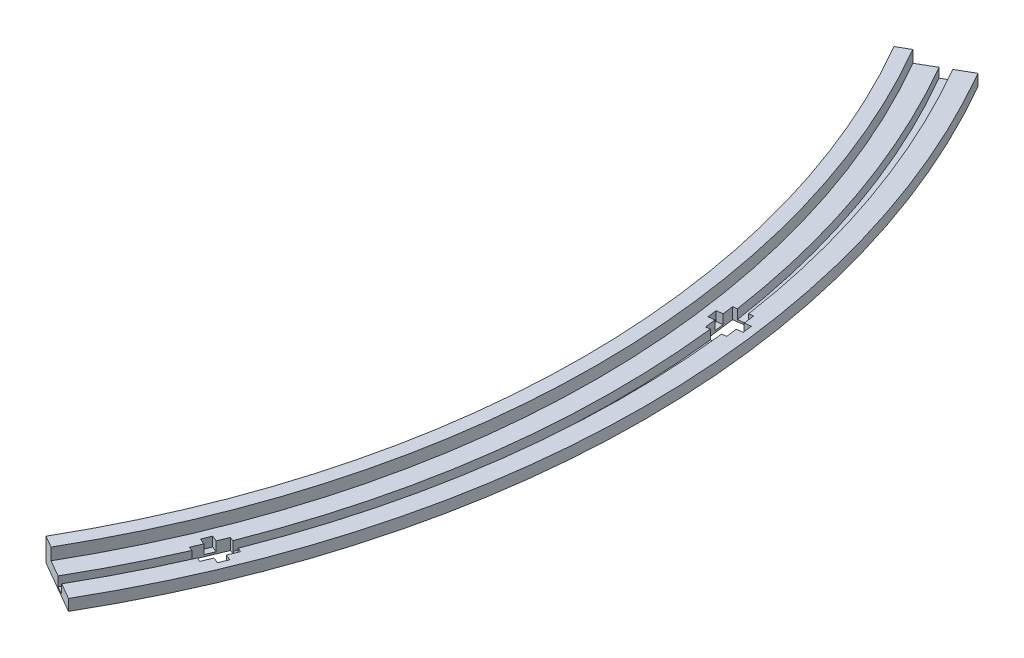
SolidWorks part; units mm, degrees
ref_plane "Ebene vorne" through (0, 0, 0) normal (0, 0, 1) x (1, 0, 0)
ref_plane "Ebene oben" through (0, 0, 0) normal (0, 1, 0) x (1, 0, 0)
ref_plane "Ebene rechts" through (0, 0, 0) normal (1, 0, 0) x (0, 0, -1)
sketch "Skizze1" plane through (0, 0, 0) normal (0, 1, 0) x (1, 0, 0)
  line L0 (0, 0) -> (290, 0) construction
  line L1 (251.1474, 145) -> (234.1733, 135.2)
  line L2 (234.1733, -135.2) -> (251.1474, -145)
  line L3 (0, 0) -> (251.1474, 145) construction
  line L4 (0, 0) -> (251.1474, -145) construction
  arc A0 (234.1733, -135.2) -> (234.1733, 135.2) centre (0, 0) ccw
  arc A1 (251.1474, -145) -> (251.1474, 145) centre (0, 0) ccw
  dimension "D1" = 290
  dimension "D2" = 270.4
  dimension "D5" = 30
  dimension "D6" = 30
extrude "Aufsatz-Linear austragen1" add sketch "Skizze1" along normal blind 3.6
sketch "Skizze2" plane through (0, 3.6, 0) normal (0, 1, 0) x (1, 0, 0)
  line L0 (234.1733, -135.2) -> (251.1474, -145) construction
  line L1 (251.1474, 145) -> (234.1733, 135.2) construction
  line L3 (243.2665, 140.45) -> (246.0378, 142.05)
  line L4 (243.2665, -140.45) -> (246.0378, -142.05)
  arc A2 (243.2665, -140.45) -> (243.2665, 140.45) centre (0, 0) ccw
  arc A3 (246.0378, -142.05) -> (246.0378, 142.05) centre (0, 0) ccw
  dimension "D1" = 5.9
  dimension "D2" = 3.2
extrude "Schnitt-Linear austragen1" cut sketch "Skizze2" against normal blind 3
sketch "Skizze3" plane through (0, 3.6, 0) normal (0, 1, 0) x (1, 0, 0)
  line L0 (234.1733, -135.2) -> (243.2665, -140.45) construction
  line L1 (243.2665, 140.45) -> (234.1733, 135.2) construction
  line L2 (0, 0) -> (280.0832, 36.8736) construction
  line L3 (0, 0) -> (290, 0) construction
  line L4 (0, 0) -> (260.996, -108.1081) construction
  line L9 (276.4562, 41.4393) -> (282.4049, 42.2225)
  line L10 (256.3109, -111.5794) -> (261.8542, -113.8755)
  line L11 (261.8542, -113.8755) -> (265.681, -104.6367)
  line L12 (265.681, -104.6367) -> (260.1377, -102.3406)
  line L13 (260.1377, -102.3406) -> (256.3109, -111.5794)
  line L14 (256.3109, -111.5794) -> (265.681, -104.6367) construction
  line L15 (282.4049, 42.2225) -> (283.7101, 32.308)
  line L16 (283.7101, 32.308) -> (277.7615, 31.5248)
  line L17 (277.7615, 31.5248) -> (276.4562, 41.4393)
  line L18 (277.7615, 31.5248) -> (282.4049, 42.2225) construction
  arc A1 (244.6522, -141.25) -> (244.6522, 141.25) centre (0, 0) ccw construction
  arc A2 (251.1474, -145) -> (251.1474, 145) centre (0, 0) ccw construction
  point P11 (280.0832, 36.8736)
  point P23 (260.996, -108.1081)
  dimension "D1" = 30
  dimension "D2" = 282.5
  dimension "D3" = 10
  dimension "D4" = 22.5
  dimension "D5" = 6
extrude "Schnitt-Linear austragen2" cut sketch "Skizze3" against normal through all
sketch "Skizze4" plane through (0, 3.6, 0) normal (0, 1, 0) x (1, 0, 0)
  line L17 (256.3109, -111.5794) -> (265.681, -104.6367) construction
  line L18 (256.9506, -104.8088) -> (266.1894, -108.6357)
  line L19 (277.7615, 31.5248) -> (282.4049, 42.2225) construction
  line L20 (274.9302, 37.7082) -> (284.8446, 39.0134)
  line L21 (284.8446, 39.0134) -> (285.2362, 36.0391)
  line L22 (285.2362, 36.0391) -> (275.3217, 34.7339)
  line L23 (275.3217, 34.7339) -> (274.9302, 37.7082)
  line L24 (275.3217, 34.7339) -> (284.8446, 39.0134) construction
  line L27 (280.9732, 42.034) -> (277.8001, 41.6162) construction
  line L31 (266.1894, -108.6357) -> (265.0413, -111.4073)
  line L32 (265.0413, -111.4073) -> (255.8025, -107.5805)
  line L33 (255.8025, -107.5805) -> (256.9506, -104.8088)
  line L34 (260.1377, -102.3406) -> (256.3109, -111.5794) construction
  line L35 (257.5632, -112.0981) -> (260.5201, -113.3229) construction
  line L36 (256.9506, -104.8088) -> (265.0413, -111.4073) construction
  point P16 (260.996, -108.1081)
  point P17 (260.996, -108.1081)
  point P21 (280.0832, 36.8736)
  point P22 (280.0832, 36.8736)
  dimension "D1" = 10
  dimension "D2" = 3
extrude "Schnitt-Linear austragen3" cut sketch "Skizze4" against normal blind 3
sketch "Skizze5" plane through (0, 3.6, 0) normal (0, 1, 0) x (1, 0, 0)
  line L0 (234.1733, 135.2) -> (237.9838, 137.4)
  line L1 (234.1733, -135.2) -> (237.9838, -137.4)
  line L2 (243.2665, 140.45) -> (234.1733, 135.2) construction
  line L4 (234.1733, -135.2) -> (243.2665, -140.45) construction
  arc A0 (237.9838, -137.4) -> (237.9838, 137.4) centre (0, 0) ccw
  arc A1 (234.1733, -135.2) -> (234.1733, 135.2) centre (0, 0) ccw
  dimension "D1" = 4.4
extrude "Aufsatz-Linear austragen2" add sketch "Skizze5" along normal blind 3.8
equation "\"D6@Skizze1\"=\"D5@Skizze1\""
